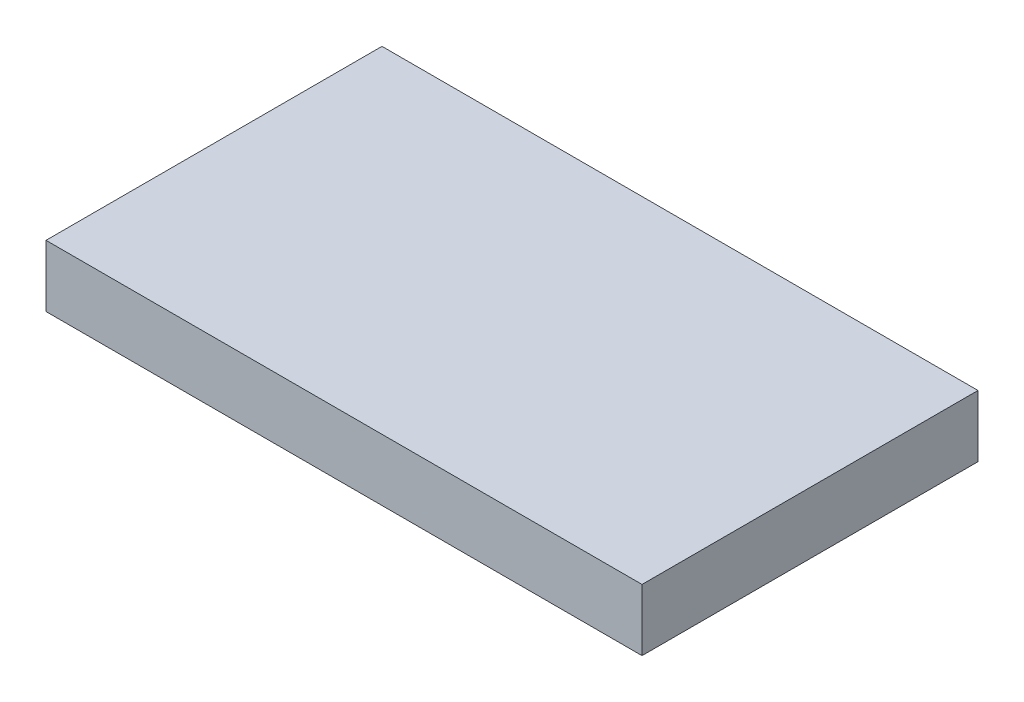
SolidWorks part; units mm, degrees
material "ESC"
ref_plane "Front Plane" through (0, 0, 0) normal (0, 0, 1) x (1, 0, 0)
ref_plane "Top Plane" through (0, 0, 0) normal (0, 1, 0) x (1, 0, 0)
ref_plane "Right Plane" through (0, 0, 0) normal (1, 0, 0) x (0, 0, -1)
sketch "Sketch1" plane through (0, 0, 0) normal (0, 1, 0) x (1, 0, 0)
  line L1 (0, 0) -> (31.9024, 0)
  line L2 (0, 0) -> (0, 17.9832)
  line L3 (0, 17.9832) -> (31.9024, 17.9832)
  line L4 (31.9024, 0) -> (31.9024, 17.9832)
  dimension "D1" = 31.9024
  dimension "D2" = 17.9832
extrude "Boss-Extrude1" add sketch "Sketch1" along normal blind 3.302
